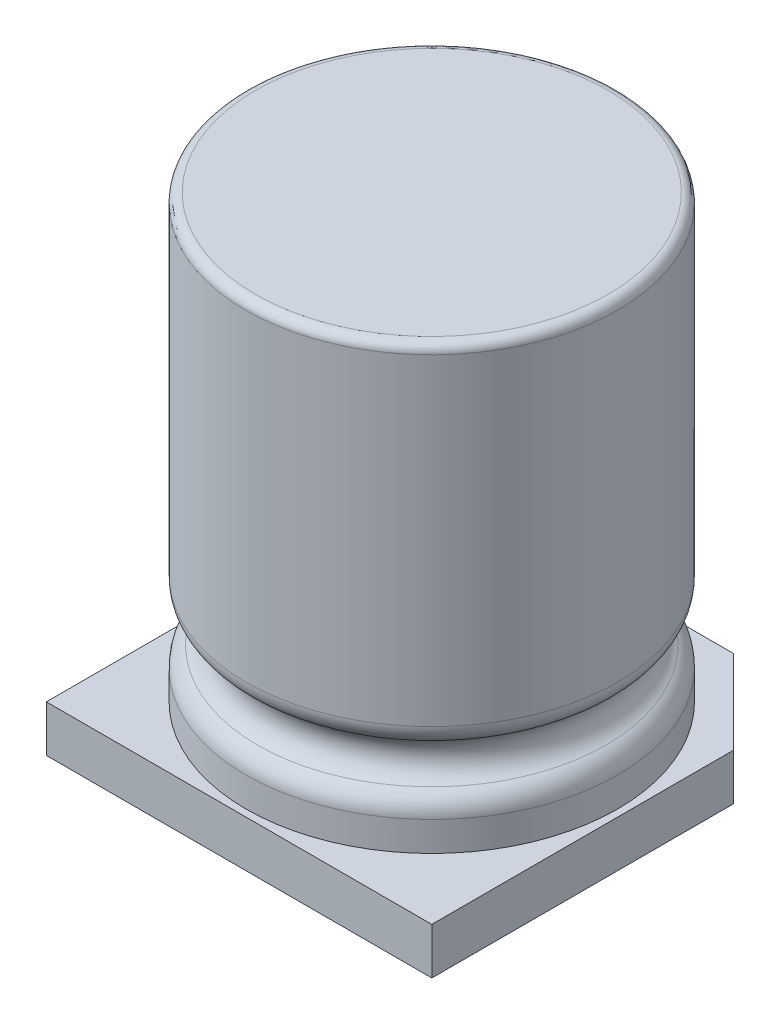
SolidWorks part; units mm, degrees
ref_plane "Front Plane" through (0, 0, 0) normal (0, 0, 1) x (1, 0, 0)
ref_plane "Top Plane" through (0, 0, 0) normal (0, 1, 0) x (1, 0, 0)
ref_plane "Right Plane" through (0, 0, 0) normal (1, 0, 0) x (0, 0, -1)
sketch "Sketch1" plane through (0, 0, 0) normal (0, 1, 0) x (1, 0, 0)
  line L1 (-4.15, 4.15) -> (4.15, 4.15)
  line L2 (-4.15, 4.15) -> (-4.15, -4.15)
  line L3 (-4.15, -4.15) -> (4.15, -4.15)
  line L4 (4.15, 4.15) -> (4.15, -4.15)
  line L5 (-4.15, 4.15) -> (4.15, -4.15) construction
  line L6 (-4.15, -4.15) -> (4.15, 4.15) construction
  point P0 (0, 0)
  dimension "D1" = 8.3
extrude "Boss-Extrude1" add sketch "Sketch1" along normal blind 1
sketch "Sketch2" plane through (0, 1, 0) normal (0, 1, 0) x (1, 0, 0)
  circle A0 centre (0, 0) radius 4
  dimension "D1" = 8
extrude "Boss-Extrude2" add sketch "Sketch2" along normal blind 9.5 separate body
sketch "Sketch3" plane through (0, 0, 0) normal (0, 0, 1) x (1, 0, 0)
  line L0 (4, 1) -> (4, 2.5) construction
  circle A0 centre (4, 2.5) radius 0.5
  point P2 (4, 2)
  point P4 (0, 0)
  dimension "D1" = 1
  dimension "D2" = 1
revolve "Cut-Revolve1" cut sketch "Sketch3" angle 360 about axis through (0, 10.5, 0) along (0, -1, 0)
fillet "Fillet1" radius 0.5 2 edges at (0, 2, 4) (0, 3, -4)
fillet "Fillet2" radius 0.2 1 edges at (0, 10.5, 4)
chamfer "Chamfer1" distance 1.8 angle 45 2 edges at (4.15, 0.5, -4.15) (-4.15, 0.5, -4.15)
